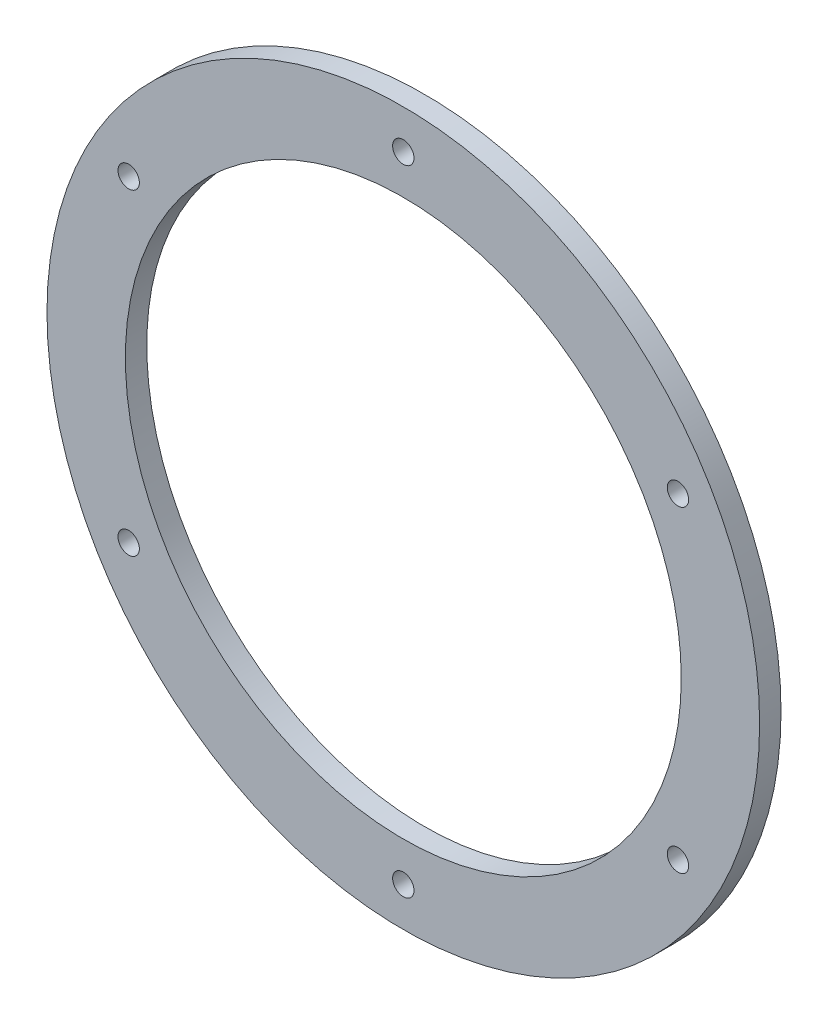
SolidWorks part; units mm, degrees
ref_plane "前视基准面" through (0, 0, 0) normal (0, 0, 1) x (1, 0, 0)
ref_plane "上视基准面" through (0, 0, 0) normal (0, 1, 0) x (1, 0, 0)
ref_plane "右视基准面" through (0, 0, 0) normal (1, 0, 0) x (0, 0, -1)
other "Configuration Table"
sketch "草图1" plane through (0, 0, 0) normal (0, 0, 1) x (1, 0, 0)
  circle A0 centre (0, 0) radius 39
  circle A1 centre (0, 0) radius 50
  dimension "D1" = 78
  dimension "D2" = 100
extrude "凸台-拉伸1" add sketch "草图1" along normal blind 3
sketch "草图2" plane through (0, 0, 3) normal (0, 0, 1) x (1, 0, 0)
  circle A0 centre (0, 0) radius 44.5 construction
  circle A1 centre (0, 44.5) radius 1.5
  circle A3 centre (38.5381, 22.25) radius 1.5
  circle A4 centre (38.5381, -22.25) radius 1.5
  circle A5 centre (0, -44.5) radius 1.5
  circle A6 centre (-38.5381, -22.25) radius 1.5
  circle A7 centre (-38.5381, 22.25) radius 1.5
  point P6 (-43.4758, -30.8023)
  point P7 (0, 0)
  point P17 (0, 0)
  dimension "D1" = 89
  dimension "D2" = 3
  dimension "D3" = 6
extrude "切除-拉伸1" cut sketch "草图2" against normal blind 3
